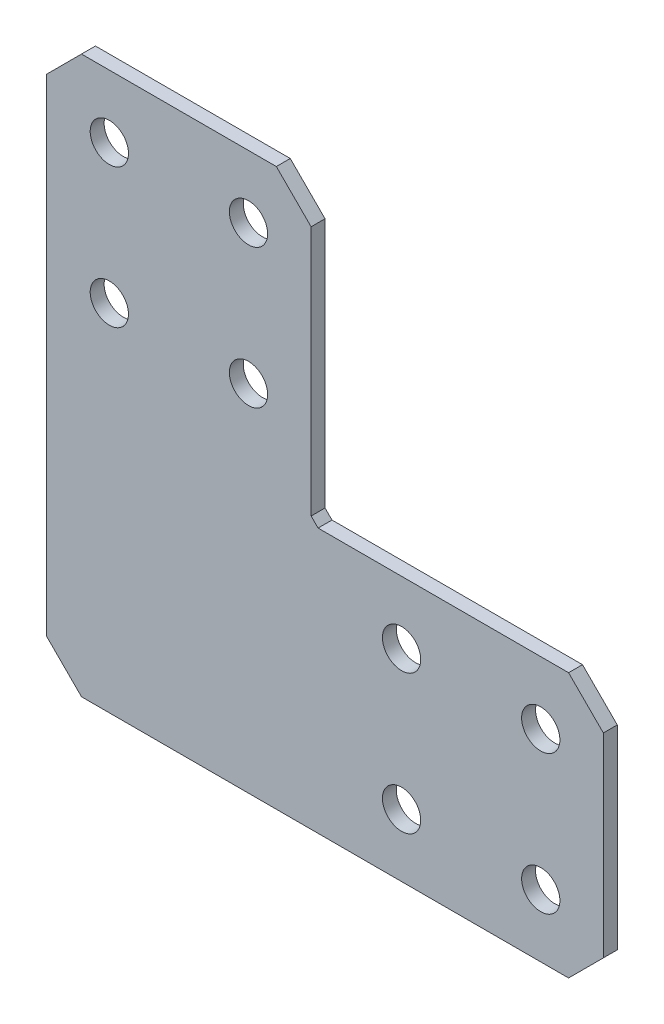
SolidWorks part; units mm, degrees
ref_plane "Front Plane" through (0, 0, 0) normal (0, 0, 1) x (1, 0, 0)
ref_plane "Top Plane" through (0, 0, 0) normal (0, 1, 0) x (1, 0, 0)
ref_plane "Right Plane" through (0, 0, 0) normal (1, 0, 0) x (0, 0, -1)
sketch "Sketch1" plane through (0, 0, 0) normal (0, 0, 1) x (1, 0, 0)
  line L0 (51, 29) -> (71, 29) construction
  line L1 (5, 0) -> (38, 0)
  line L2 (0, 5) -> (0, 75)
  line L3 (5, 80) -> (33, 80)
  line L4 (38, 39) -> (38, 75)
  line L5 (38, 0) -> (75, 0)
  line L6 (9, 71) -> (29, 71) construction
  line L7 (39, 38) -> (75, 38)
  line L8 (80, 5) -> (80, 33)
  line L9 (9, 71) -> (9, 51) construction
  line L10 (9, 51) -> (29, 51) construction
  line L11 (29, 71) -> (29, 51) construction
  line L12 (51, 29) -> (51, 9) construction
  line L13 (51, 9) -> (71, 9) construction
  line L14 (71, 29) -> (71, 9) construction
  line L15 (0, 75) -> (5, 80)
  line L16 (33, 80) -> (38, 75)
  line L17 (75, 38) -> (80, 33)
  line L18 (75, 0) -> (80, 5)
  line L19 (39, 38) -> (38, 39)
  line L20 (0, 5) -> (5, 0)
  circle A0 centre (9, 71) radius 2.75
  circle A1 centre (29, 71) radius 2.75
  circle A2 centre (29, 51) radius 2.75
  circle A3 centre (9, 51) radius 2.75
  circle A4 centre (51, 29) radius 2.75
  circle A5 centre (71, 29) radius 2.75
  circle A6 centre (71, 9) radius 2.75
  circle A7 centre (51, 9) radius 2.75
  point P0 (0, 0)
  point P1 (38, 80)
  point P2 (0, 80)
  point P5 (80, 38)
  point P6 (38, 38)
  point P7 (80, 0)
  dimension "D6" = 5.5
  dimension "D8" = 5.5
  dimension "D1" = 38
  dimension "D2" = 38
  dimension "D3" = 80
  dimension "D4" = 80
  dimension "D5" = 20
  dimension "D7" = 20
  dimension "D9" = 9
  dimension "D10" = 9
  dimension "D11" = 9
  dimension "D12" = 9
extrude "Boss-Extrude1" add sketch "Sketch1" along normal blind 2
